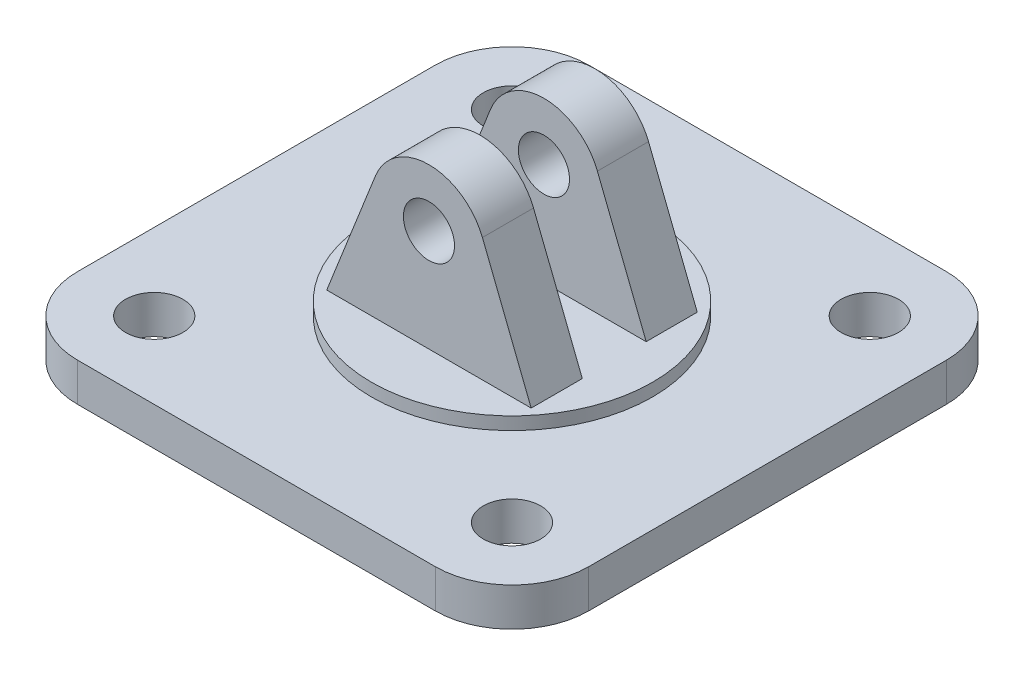
SolidWorks part; units mm, degrees
ref_plane "Front Plane" through (0, 0, 0) normal (0, 0, 1) x (1, 0, 0)
ref_plane "Top Plane" through (0, 0, 0) normal (0, 1, 0) x (1, 0, 0)
ref_plane "Right Plane" through (0, 0, 0) normal (1, 0, 0) x (0, 0, -1)
sketch "Sketch1" plane through (0, 0, 0) normal (0, 1, 0) x (1, 0, 0)
  line L1 (-50, -50) -> (50, -50)
  line L2 (-50, -50) -> (-50, 50)
  line L3 (-50, 50) -> (50, 50)
  line L4 (50, -50) -> (50, 50)
  line L5 (-50, -50) -> (50, 50) construction
  line L6 (-50, 50) -> (50, -50) construction
  point P0 (0, 0)
  dimension "D1" = 100
  dimension "D2" = 100
extrude "Boss-Extrude1" add sketch "Sketch1" along normal blind 7.5
fillet "Fillet1" radius 15 4 edges at (-50, 3.75, -50) (50, 3.75, -50) (50, 3.75, 50) (-50, 3.75, 50)
sketch "Sketch2" plane through (0, 7.5, 0) normal (0, 1, 0) x (1, 0, 0)
  line L0 (0, 0) -> (0, 40.0209) construction
  line L1 (0, 0) -> (-40.0209, 0) construction
  circle A0 centre (-35, 35) radius 5.625
  circle A1 centre (35, 35) radius 5.625
  circle A2 centre (35, -35) radius 5.625
  circle A3 centre (-35, -35) radius 5.625
  dimension "D1" = 11.25
  dimension "D2" = 35
  dimension "D3" = 35
extrude "Cut-Extrude1" cut sketch "Sketch2" against normal blind 7.5
sketch "Sketch3" plane through (0, 7.5, 0) normal (0, 1, 0) x (1, 0, 0)
  circle A0 centre (0, 0) radius 27.5
  dimension "D1" = 55
extrude "Boss-Extrude2" add sketch "Sketch3" along normal blind 2.5
sketch "Sketch5" plane through (0, 10, 0) normal (0, 1, 0) x (1, 0, 0)
  line L0 (0, 0) -> (0, -34.2645) construction
  line L1 (-20, -6.25) -> (20, -6.25)
  line L2 (-20, -6.25) -> (-20, -16.25)
  line L3 (-20, -16.25) -> (20, -16.25)
  line L4 (20, -6.25) -> (20, -16.25)
  line L5 (-20, -6.25) -> (20, -16.25) construction
  line L6 (-20, -16.25) -> (20, -6.25) construction
  point P0 (0, -11.25)
  dimension "D1" = 6.25
  dimension "D2" = 10
  dimension "D3" = 40
  dimension "D4" = 20
extrude "Boss-Extrude4" add sketch "Sketch5" along normal blind 40
sketch "Sketch6" plane through (0, 0, 16.25) normal (0, 0, 1) x (1, 0, 0)
  line L1 (-16.5217, 0) -> (21.3935, 0) construction
  line L2 (-35, 0) -> (35, 0) construction
  line L3 (-10.4627, 34.1346) -> (-20, 10)
  line L4 (-20, 10) -> (20, 10)
  line L5 (10.4627, 34.1346) -> (20, 10)
  line L6 (-20, 10) -> (-24.3589, 10)
  line L7 (27.5, 10) -> (-27.5, 10) construction
  line L8 (-20, 10) -> (20, 10)
  line L9 (-20, 10) -> (-20, 50)
  line L10 (-20, 50) -> (20, 50)
  line L11 (20, 10) -> (20, 50)
  circle A0 centre (0, 30) radius 5
  arc A1 (10.4627, 34.1346) -> (-10.4627, 34.1346) centre (0, 30) ccw
  line M6 (20, 10) -> (20, 50)
  line M7 (20, 50) -> (-20, 50)
  line M8 (-20, 50) -> (-20, 10)
  dimension "D1" = 10
  dimension "D3" = 22.5
  dimension "D2" = 30
  dimension "D4" = 40
  dimension "D5" = 30
extrude "Cut-Extrude2" cut sketch "Sketch6" against normal blind 10 contours A1 L5 L3 M6 M7 M8 | A0
mirror "Mirror4" about plane through (0, 0, 0) normal (0, 0, 1) of "Cut-Extrude2", "Boss-Extrude4"
sketch "Sketch7" plane through (0, 0, 0) normal (0, -1, 0) x (1, 0, 0)
  line L1 (-20, -25) -> (20, -25)
  line L2 (-25, -20) -> (-25, 20)
  line L3 (-20, 25) -> (20, 25)
  line L4 (25, -20) -> (25, 20)
  line L5 (-25, -25) -> (25, 25) construction
  line L6 (-25, 25) -> (25, -25) construction
  arc A0 (-20, -25) -> (-25, -20) centre (-20, -20) cw
  arc A1 (20, -25) -> (25, -20) centre (20, -20) ccw
  arc A2 (25, 20) -> (20, 25) centre (20, 20) ccw
  arc A3 (-20, 25) -> (-25, 20) centre (-20, 20) ccw
  point P0 (0, 0)
  dimension "D3" = 5
  dimension "D1" = 50
  dimension "D2" = 50
extrude "Cut-Extrude3" cut sketch "Sketch7" against normal blind 1.875
